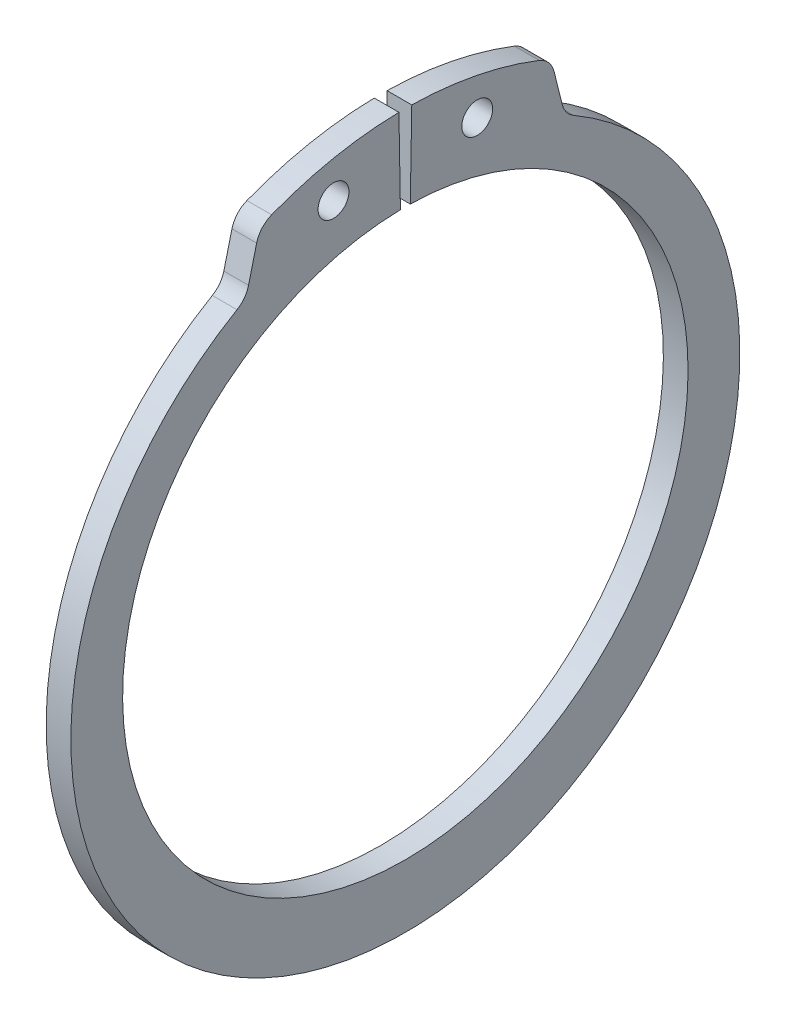
SolidWorks part; units mm, degrees
material "Cast Carbon Steel"
ref_plane "Front" through (0, 0, 0) normal (0, 0, 1) x (1, 0, 0)
ref_plane "Top" through (0, 0, 0) normal (0, 1, 0) x (1, 0, 0)
ref_plane "Right" through (0, 0, 0) normal (1, 0, 0) x (0, 0, -1)
sketch "Sketch1" plane through (0, 0, 0) normal (1, 0, 0) x (0, 0, -1)
  line L0 (0, 0) -> (0, 22.9) construction
  line L1 (-0.3997, 22.8965) -> (-0.5201, 29.7955)
  line L2 (-0.5201, 29.7955) -> (-11.2409, 29.6083) construction
  line L3 (-11.2409, 29.6083) -> (-12.9101, 22.9133) construction
  line L4 (0.5201, 29.7955) -> (0.3997, 22.8965)
  line L5 (0.5201, 29.7955) -> (11.2409, 29.6083) construction
  line L6 (11.2409, 29.6083) -> (12.9101, 22.9133) construction
  line L7 (-12.9101, 22.9133) -> (-11.2411, 19.9511) construction
  line L8 (12.9101, 22.9133) -> (11.2411, 19.9511) construction
  line L9 (0, -22.9) -> (0, -28) construction
  line L10 (-11.2409, 29.6083) -> (-0.3997, 22.8965) construction
  line L11 (-22.9, 0) -> (22.9, 0) construction
  line L12 (0, 22.9) -> (0, 29.8) construction
  line L13 (11.8004, 27.364) -> (12.9101, 22.9133)
  line L14 (-11.8004, 27.364) -> (-12.9101, 22.9133)
  circle A0 centre (0, 0) radius 22.9 construction
  arc A1 (-0.3997, 22.8965) -> (0.3997, 22.8965) centre (0, 0) ccw
  circle A2 centre (0, -0.9065) radius 27.0935 construction
  circle A4 centre (-5.8203, 26.2524) radius 1.25
  circle A5 centre (5.8203, 26.2524) radius 1.25
  arc A6 (-12.9101, 22.9133) -> (12.9101, 22.9133) centre (0, -0.9065) ccw
  arc A7 (0.5201, 29.7955) -> (11.8004, 27.364) centre (0, 0) cw
  arc A8 (-0.5201, 29.7955) -> (-11.8004, 27.364) centre (0, 0) ccw
  dimension "A" = 45.8
  dimension "Hole" = 2.5
  dimension "Smin" = 3.4
  dimension "D1" = 75
  dimension "Angle" = 1
  dimension "H" = 6.9
extrude "Extrude1" add sketch "Sketch1" along normal mid plane 2
fillet "Fillet1" radius 2 4 edges at (0, 22.9133, 12.9101) (0, 27.364, 11.8004) (0, 27.364, -11.8004) (0, 22.9133, -12.9101)
sketch "Sketch2" plane through (0, 0, 0) normal (0, 0, 1) x (1, 0, 0)
  line L0 (-5.375, 0) -> (16.125, 0)
  line L1 (16.125, 0) -> (16.125, -25)
  line L2 (-5.375, 0) -> (-5.375, -23.5)
  line L3 (16.125, -25) -> (1.075, -25)
  line L4 (1.075, -25) -> (1.075, -23.5)
  line L5 (1.075, -23.5) -> (-1.075, -23.5)
  line L6 (-1.075, -23.5) -> (-1.075, -25)
  line L7 (-1.075, -25) -> (-5.375, -25) construction
  line L8 (-5.375, -25) -> (-5.375, 0) construction
  line L9 (0, -23.5) -> (0, 0) construction
  line L10 (16.125, 0) -> (14.0551, 0) construction
  line L11 (-5.375, -23.5) -> (-3.875, -25)
  line L12 (-3.875, -25) -> (-1.075, -25)
  dimension "D2" = 21.5
  dimension "D3" = 5.375
  dimension "D1" = 45
revolve "Revolve1" [suppressed] add sketch "Sketch2" angle 360 about L10
equation "\"D2@Sketch2\" = \"W@Sketch2\"*10"
equation "\"D3@Sketch2\" = \"D2@Sketch2\"/4"
equation "\"Smin@Sketch1\" = \"Smax@Sketch1\"/1.5"
equation "\"D1@Fillet1\" = \"D1@Extrude1\""
